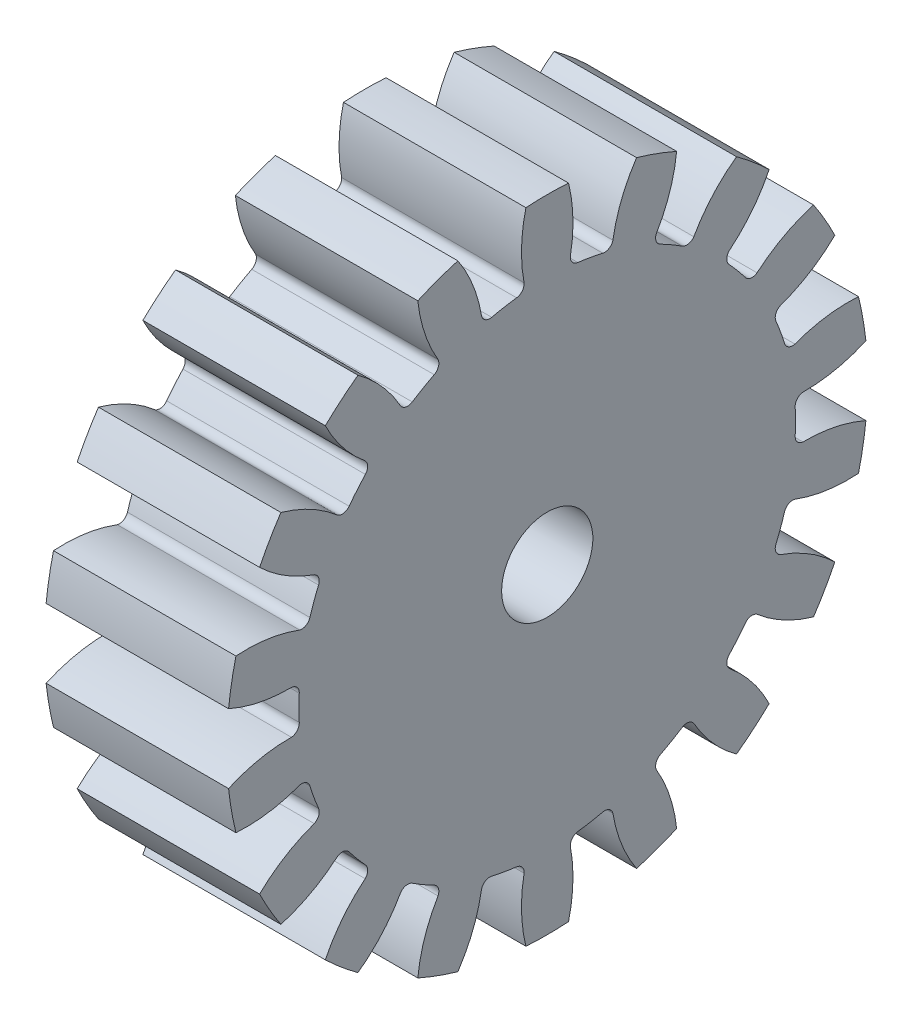
SolidWorks part; units mm, degrees
ref_plane "Front" through (0, 0, 0) normal (0, 0, 1) x (1, 0, 0)
ref_plane "Top" through (0, 0, 0) normal (0, 1, 0) x (1, 0, 0)
ref_plane "Right" through (0, 0, 0) normal (1, 0, 0) x (0, 0, -1)
ref_plane "Plane1" through (-5.0626, 0, 0) normal (-1, 0, 0) x (0, -1, 0)
sketch "Sketch1" plane through (-5.0626, 0, 0) normal (-1, 0, 0) x (0, -1, 0)
  circle A0 centre (0, 0) radius 1.5
  arc A1 (-4.9227, -6.5141) -> (-4.8627, -6.8998) centre (-5.0918, -6.7379) cw
  arc A2 (-5.8657, -8.7582) -> (-4.8627, -6.8998) centre (-1.103, -10.1288) cw
  arc A3 (-5.8657, -8.7582) -> (-4.652, -9.459) centre (0, 0) ccw
  arc A4 (-3.544, -7.6611) -> (-4.652, -9.459) centre (-8.2005, -6.0318) cw
  arc A5 (-3.544, -7.6611) -> (-3.18, -7.5203) centre (-3.2893, -7.7786) cw
  arc A6 (-3.18, -7.5203) -> (-2.3979, -7.805) centre (0, 0) ccw
  arc A7 (-2.3979, -7.805) -> (-2.2096, -8.1468) centre (-2.4803, -8.0731) cw
  arc A8 (-2.5165, -10.2362) -> (-2.2096, -8.1468) centre (2.4278, -9.8952) cw
  arc A9 (-2.5165, -10.2362) -> (-1.1363, -10.4796) centre (0, 0) ccw
  arc A10 (-0.71, -8.4112) -> (-1.1363, -10.4796) centre (-5.643, -8.4728) cw
  arc A11 (-0.71, -8.4112) -> (-0.4162, -8.1544) centre (-0.4305, -8.4345) cw
  arc A12 (-0.4162, -8.1544) -> (0.4162, -8.1544) centre (0, 0) ccw
  arc A13 (0.4162, -8.1544) -> (0.71, -8.4112) centre (0.4305, -8.4345) cw
  arc A14 (1.1363, -10.4796) -> (0.71, -8.4112) centre (5.6657, -8.4681) cw
  arc A15 (1.1363, -10.4796) -> (2.5165, -10.2362) centre (0, 0) ccw
  arc A16 (2.2096, -8.1468) -> (2.5165, -10.2362) centre (-2.4048, -9.8918) cw
  arc A17 (2.2096, -8.1468) -> (2.3979, -7.805) centre (2.4803, -8.0731) cw
  arc A18 (2.3979, -7.805) -> (3.18, -7.5203) centre (0, 0) ccw
  arc A19 (3.18, -7.5203) -> (3.544, -7.6611) centre (3.2893, -7.7786) cw
  arc A20 (4.652, -9.459) -> (3.544, -7.6611) centre (8.2203, -6.0196) cw
  arc A21 (4.652, -9.459) -> (5.8657, -8.7582) centre (0, 0) ccw
  arc A22 (4.8627, -6.8998) -> (5.8657, -8.7582) centre (1.1234, -10.1177) cw
  arc A23 (4.8627, -6.8998) -> (4.9227, -6.5141) centre (5.0918, -6.7379) cw
  arc A24 (4.9227, -6.5141) -> (5.5604, -5.9791) centre (0, 0) ccw
  arc A25 (5.5604, -5.9791) -> (5.9505, -5.987) centre (5.7514, -6.1845) cw
  arc A26 (7.6066, -7.2974) -> (5.9505, -5.987) centre (9.7834, -2.8451) cw
  arc A27 (7.6066, -7.2974) -> (8.5075, -6.2238) centre (0, 0) ccw
  arc A28 (6.9293, -4.8205) -> (8.5075, -6.2238) centre (4.5161, -9.1233) cw
  arc A29 (6.9293, -4.8205) -> (6.8538, -4.4376) centre (7.0893, -4.5901) cw
  arc A30 (6.8538, -4.4376) -> (7.27, -3.7168) centre (0, 0) ccw
  arc A31 (7.27, -3.7168) -> (7.6394, -3.5907) centre (7.5198, -3.8445) cw
  arc A32 (9.6437, -4.2558) -> (7.6394, -3.5907) centre (10.1664, 0.6726) cw
  arc A33 (9.6437, -4.2558) -> (10.1231, -2.9388) centre (0, 0) ccw
  arc A34 (8.1602, -2.1598) -> (10.1231, -2.9388) centre (7.3642, -7.0285) cw
  arc A35 (8.1602, -2.1598) -> (7.9582, -1.8259) centre (8.2316, -1.8886) cw
  arc A36 (7.9582, -1.8259) -> (8.1028, -1.0061) centre (0, 0) ccw
  arc A37 (8.1028, -1.0061) -> (8.4067, -0.7614) centre (8.3811, -1.0407) cw
  arc A38 (10.5177, -0.7008) -> (8.4067, -0.7614) centre (9.3233, 4.1092) cw
  arc A39 (10.5177, -0.7008) -> (10.5177, 0.7008) centre (0, 0) ccw
  arc A40 (8.4067, 0.7614) -> (10.5177, 0.7008) centre (9.3239, -4.086) cw
  arc A41 (8.4067, 0.7614) -> (8.1028, 1.0061) centre (8.3811, 1.0407) cw
  arc A42 (8.1028, 1.0061) -> (7.9582, 1.8259) centre (0, 0) ccw
  arc A43 (7.9582, 1.8259) -> (8.1602, 2.1598) centre (8.2316, 1.8886) cw
  arc A44 (10.1231, 2.9388) -> (8.1602, 2.1598) centre (7.3556, 7.0501) cw
  arc A45 (10.1231, 2.9388) -> (9.6437, 4.2558) centre (0, 0) ccw
  arc A46 (7.6394, 3.5907) -> (9.6437, 4.2558) centre (10.1591, -0.6506) cw
  arc A47 (7.6394, 3.5907) -> (7.27, 3.7168) centre (7.5198, 3.8445) cw
  arc A48 (7.27, 3.7168) -> (6.8538, 4.4376) centre (0, 0) ccw
  arc A49 (6.8538, 4.4376) -> (6.9293, 4.8205) centre (7.0893, 4.5901) cw
  arc A50 (8.5075, 6.2238) -> (6.9293, 4.8205) centre (4.5007, 9.1407) cw
  arc A51 (8.5075, 6.2238) -> (7.6066, 7.2974) centre (0, 0) ccw
  arc A52 (5.9505, 5.987) -> (7.6066, 7.2974) centre (9.769, 2.8633) cw
  arc A53 (5.9505, 5.987) -> (5.5604, 5.9791) centre (5.7514, 6.1845) cw
  arc A54 (5.5604, 5.9791) -> (4.9227, 6.5141) centre (0, 0) ccw
  arc A55 (4.9227, 6.5141) -> (4.8627, 6.8998) centre (5.0918, 6.7379) cw
  arc A56 (5.8657, 8.7582) -> (4.8627, 6.8998) centre (1.103, 10.1288) cw
  arc A57 (5.8657, 8.7582) -> (4.652, 9.459) centre (0, 0) ccw
  arc A58 (3.544, 7.6611) -> (4.652, 9.459) centre (8.2005, 6.0318) cw
  arc A59 (3.544, 7.6611) -> (3.18, 7.5203) centre (3.2893, 7.7786) cw
  arc A60 (3.18, 7.5203) -> (2.3979, 7.805) centre (0, 0) ccw
  arc A61 (2.3979, 7.805) -> (2.2096, 8.1468) centre (2.4803, 8.0731) cw
  arc A62 (2.5165, 10.2362) -> (2.2096, 8.1468) centre (-2.4278, 9.8952) cw
  arc A63 (2.5165, 10.2362) -> (1.1363, 10.4796) centre (0, 0) ccw
  arc A64 (0.71, 8.4112) -> (1.1363, 10.4796) centre (5.643, 8.4728) cw
  arc A65 (0.71, 8.4112) -> (0.4162, 8.1544) centre (0.4305, 8.4345) cw
  arc A66 (0.4162, 8.1544) -> (-0.4162, 8.1544) centre (0, 0) ccw
  arc A67 (-0.4162, 8.1544) -> (-0.71, 8.4112) centre (-0.4305, 8.4345) cw
  arc A68 (-1.1363, 10.4796) -> (-0.71, 8.4112) centre (-5.6657, 8.4681) cw
  arc A69 (-1.1363, 10.4796) -> (-2.5165, 10.2362) centre (0, 0) ccw
  arc A70 (-2.2076, 8.1389) -> (-2.5165, 10.2362) centre (2.4047, 9.8897) cw
  arc A71 (-2.2076, 8.1389) -> (-2.3979, 7.805) centre (-2.4803, 8.0731) cw
  arc A72 (-2.3979, 7.805) -> (-3.18, 7.5203) centre (0, 0) ccw
  arc A73 (-3.18, 7.5203) -> (-3.544, 7.6611) centre (-3.2893, 7.7786) cw
  arc A74 (-4.652, 9.459) -> (-3.544, 7.6611) centre (-8.2203, 6.0196) cw
  arc A75 (-4.652, 9.459) -> (-5.8657, 8.7582) centre (0, 0) ccw
  arc A76 (-4.8627, 6.8998) -> (-5.8657, 8.7582) centre (-1.1234, 10.1177) cw
  arc A77 (-4.8627, 6.8998) -> (-4.9227, 6.5141) centre (-5.0918, 6.7379) cw
  arc A78 (-4.9227, 6.5141) -> (-5.5604, 5.9791) centre (0, 0) ccw
  arc A79 (-5.5604, 5.9791) -> (-5.9505, 5.987) centre (-5.7514, 6.1845) cw
  arc A80 (-7.6066, 7.2974) -> (-5.9505, 5.987) centre (-9.7834, 2.8451) cw
  arc A81 (-7.6066, 7.2974) -> (-8.5075, 6.2238) centre (0, 0) ccw
  arc A82 (-6.9293, 4.8205) -> (-8.5075, 6.2238) centre (-4.5161, 9.1233) cw
  arc A83 (-6.9293, 4.8205) -> (-6.8538, 4.4376) centre (-7.0893, 4.5901) cw
  arc A84 (-6.8538, 4.4376) -> (-7.27, 3.7168) centre (0, 0) ccw
  arc A85 (-7.27, 3.7168) -> (-7.6394, 3.5907) centre (-7.5198, 3.8445) cw
  arc A86 (-9.6437, 4.2558) -> (-7.6394, 3.5907) centre (-10.1664, -0.6726) cw
  arc A87 (-9.6437, 4.2558) -> (-10.1231, 2.9388) centre (0, 0) ccw
  arc A88 (-8.1602, 2.1598) -> (-10.1231, 2.9388) centre (-7.3642, 7.0285) cw
  arc A89 (-8.1602, 2.1598) -> (-7.9582, 1.8259) centre (-8.2316, 1.8886) cw
  arc A90 (-7.9582, 1.8259) -> (-8.1028, 1.0061) centre (0, 0) ccw
  arc A91 (-8.1028, 1.0061) -> (-8.4067, 0.7614) centre (-8.3811, 1.0407) cw
  arc A92 (-10.5177, 0.7008) -> (-8.4067, 0.7614) centre (-9.3233, -4.1092) cw
  arc A93 (-10.5177, 0.7008) -> (-10.5177, -0.7008) centre (0, 0) ccw
  arc A94 (-8.4067, -0.7614) -> (-10.5177, -0.7008) centre (-9.3239, 4.086) cw
  arc A95 (-8.4067, -0.7614) -> (-8.1028, -1.0061) centre (-8.3811, -1.0407) cw
  arc A96 (-8.1028, -1.0061) -> (-7.9582, -1.8259) centre (0, 0) ccw
  arc A97 (-7.9582, -1.8259) -> (-8.1602, -2.1598) centre (-8.2316, -1.8886) cw
  arc A98 (-10.1231, -2.9388) -> (-8.1602, -2.1598) centre (-7.3556, -7.0501) cw
  arc A99 (-10.1231, -2.9388) -> (-9.6437, -4.2558) centre (0, 0) ccw
  arc A100 (-7.6394, -3.5907) -> (-9.6437, -4.2558) centre (-10.1591, 0.6506) cw
  arc A101 (-7.6394, -3.5907) -> (-7.27, -3.7168) centre (-7.5198, -3.8445) cw
  arc A102 (-7.27, -3.7168) -> (-6.8538, -4.4376) centre (0, 0) ccw
  arc A103 (-6.8538, -4.4376) -> (-6.9293, -4.8205) centre (-7.0893, -4.5901) cw
  arc A104 (-8.5075, -6.2238) -> (-6.9293, -4.8205) centre (-4.5007, -9.1407) cw
  arc A105 (-8.5075, -6.2238) -> (-7.6066, -7.2974) centre (0, 0) ccw
  arc A106 (-5.9505, -5.987) -> (-7.6066, -7.2974) centre (-9.769, -2.8633) cw
  arc A107 (-5.9505, -5.987) -> (-5.5604, -5.9791) centre (-5.7514, -6.1845) cw
  arc A108 (-5.5604, -5.9791) -> (-4.9227, -6.5141) centre (0, 0) ccw
  circle A109 centre (0, 0) radius 8.165 construction
  circle A110 centre (0, 0) radius 10.541 construction
  circle A111 centre (0, 0) radius 9.4921 construction
  arc A112 (-0.8117, 9.4684) -> (-4.0011, 8.6197) centre (0, 0) ccw
  point P185 (0, 0)
  dimension "D1" = 16.33
  dimension "D2" = 21.082
  dimension "D3" = 18.9842
  dimension "D4" = 2.108
  dimension "D5" = 2.376
  dimension "D6" = 3.3172
extrude "Boss-Extrude1" add sketch "Sketch1" against normal blind 6 contours A68 A112 A70 A71 A72 A73 A74 A75 A76 A77 A78 A79 A80 A81 A82 A83 A84 A85 A86 A87 A88 A89 A90 A91 A92 A93 A94 A95 A96 A97 A98 A99 A100 A101 A102 A103 A104 A105 A106 A107 A108 A1 A2 A3 A4 A5 A6 A7 A8 A9 | A0
